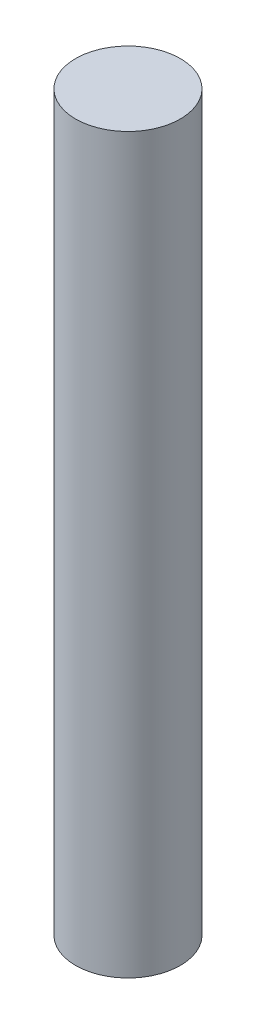
SolidWorks part; units mm, degrees
ref_plane "前视基准面" through (0, 0, 0) normal (0, 0, 1) x (1, 0, 0)
ref_plane "上视基准面" through (0, 0, 0) normal (0, 1, 0) x (1, 0, 0)
ref_plane "右视基准面" through (0, 0, 0) normal (1, 0, 0) x (0, 0, -1)
other "Configuration Table"
sketch "草图1" plane through (0, 0, 0) normal (0, 1, 0) x (1, 0, 0)
  circle A0 centre (0, 0) radius 4
  dimension "D1" = 8
extrude "凸台-拉伸1" add sketch "草图1" along normal blind 56 contours A0
